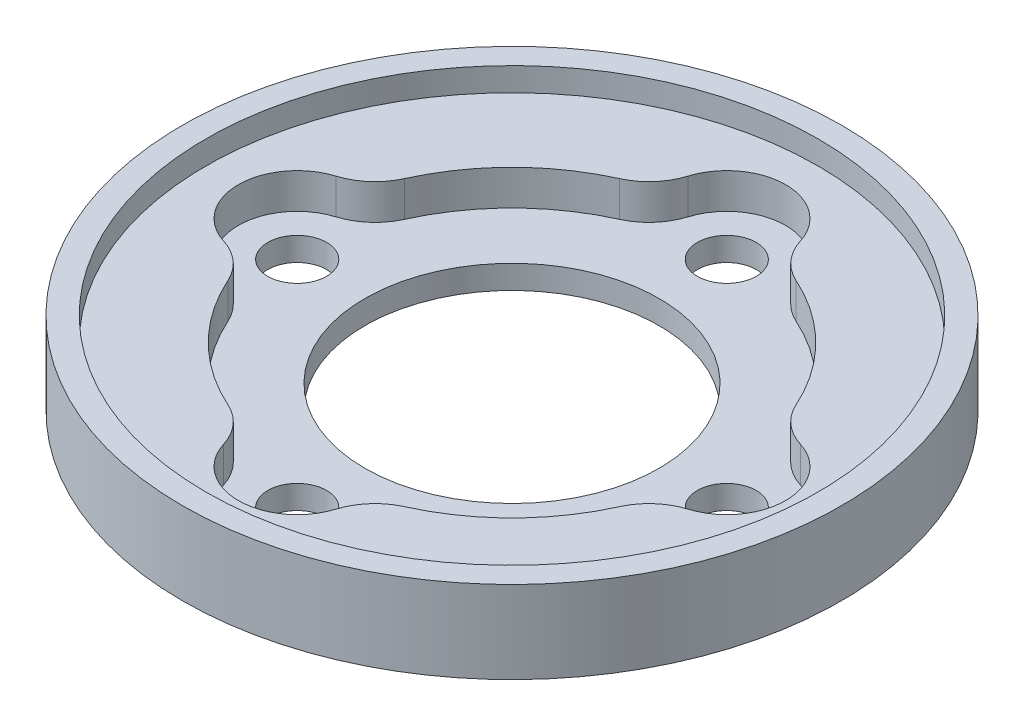
SolidWorks part; units mm, degrees
ref_plane "Front Plane" through (0, 0, 0) normal (0, 0, 1) x (1, 0, 0)
ref_plane "Top Plane" through (0, 0, 0) normal (0, 1, 0) x (1, 0, 0)
ref_plane "Right Plane" through (0, 0, 0) normal (1, 0, 0) x (0, 0, -1)
sketch "Sketch1" plane through (0, 0, 0) normal (0, 1, 0) x (1, 0, 0)
  line L0 (0, 0) -> (18.25, 0) construction
  circle A0 centre (0, 0) radius 28
  circle A1 centre (0, 0) radius 12.5
  circle A2 centre (18.25, 0) radius 2.5
  circle A4 centre (0, -18.25) radius 2.5
  circle A5 centre (-18.25, 0) radius 2.5
  circle A6 centre (0, 18.25) radius 2.5
  point P11 (0, 0)
  point P16 (0, 0)
  dimension "D1" = 56
  dimension "D2" = 25
  dimension "D4" = 5
  dimension "D3" = 18.25
  dimension "D5" = 4
extrude "Boss-Extrude1" add sketch "Sketch1" along normal blind 5
sketch "Sketch2" plane through (0, 5, 0) normal (0, 1, 0) x (1, 0, 0)
  circle A0 centre (0, 0) radius 28
  circle A1 centre (0, 0) radius 26
  dimension "D1" = 56
  dimension "D2" = 52
extrude "Boss-Extrude2" add sketch "Sketch2" along normal blind 2
sketch "Sketch4" plane through (0, 5, 0) normal (0, 1, 0) x (1, 0, 0)
  arc A4 (4.9529, 17.5651) -> (-4.9529, 17.5651) centre (0, 18.25) ccw
  arc A5 (17.5651, -4.9529) -> (17.5651, 4.9529) centre (18.25, 0) ccw
  arc A6 (-17.5651, 4.9529) -> (-17.5651, -4.9529) centre (-18.25, 0) ccw
  arc A7 (-4.9529, -17.5651) -> (4.9529, -17.5651) centre (0, -18.25) ccw
  arc A8 (-4.9529, 17.5651) -> (-17.5651, 4.9529) centre (0, 0) ccw
  arc A9 (-17.5651, -4.9529) -> (-4.9529, -17.5651) centre (0, 0) ccw
  arc A10 (4.9529, -17.5651) -> (17.5651, -4.9529) centre (0, 0) ccw
  arc A11 (17.5651, 4.9529) -> (4.9529, 17.5651) centre (0, 0) ccw
  dimension "D1" = 10
  dimension "D2" = 10
  dimension "D3" = 10
  dimension "D4" = 10
extrude "Cut-Extrude1" cut sketch "Sketch4" against normal blind 3
fillet "Fillet1" radius 5 8 edges at (-4.9529, 3.5, 17.5651) (-17.5651, 3.5, 4.9529) (4.9529, 3.5, 17.5651) (17.5651, 3.5, 4.9529) (17.5651, 3.5, -4.9529) (4.9529, 3.5, -17.5651) (-4.9529, 3.5, -17.5651) (-17.5651, 3.5, -4.9529)
